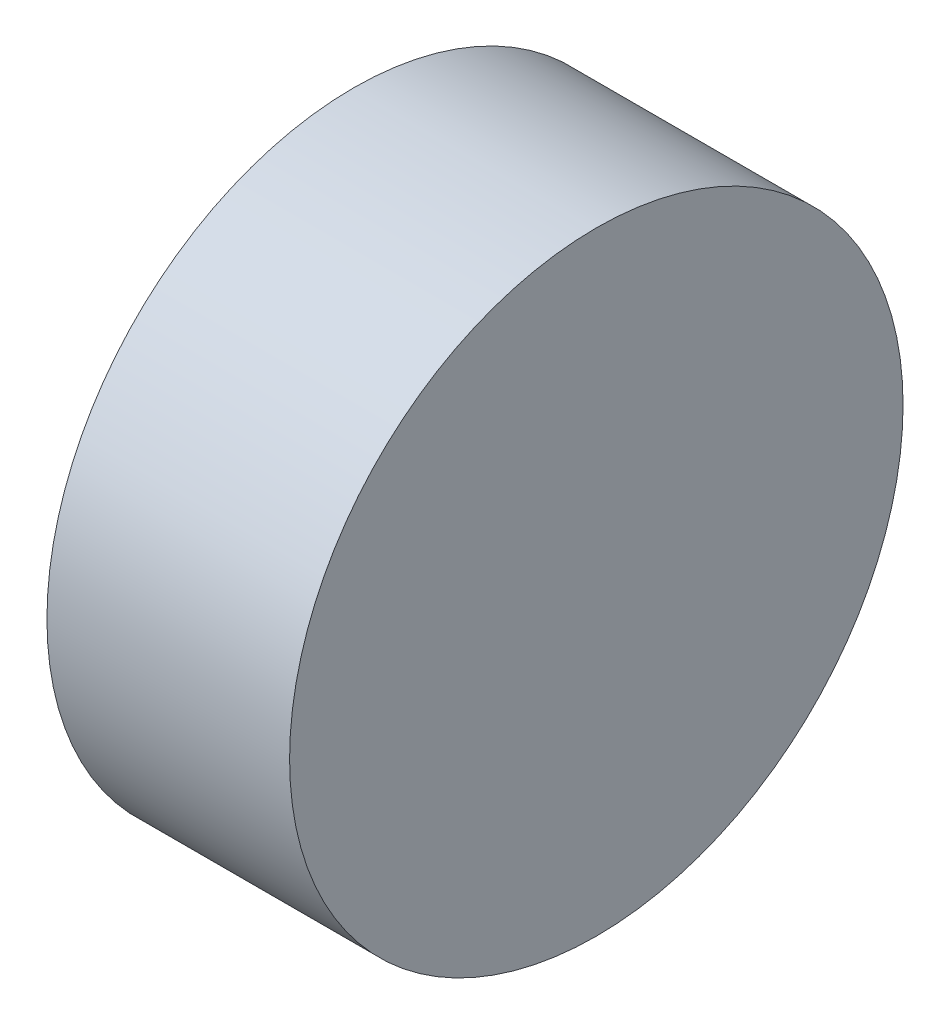
SolidWorks part; units mm, degrees
ref_plane "前视基准面" through (0, 0, 0) normal (0, 0, 1) x (1, 0, 0)
ref_plane "上视基准面" through (0, 0, 0) normal (0, 1, 0) x (1, 0, 0)
ref_plane "右视基准面" through (0, 0, 0) normal (1, 0, 0) x (0, 0, -1)
sketch "草图4" plane through (0, 0, 0) normal (1, 0, 0) x (0, 0, -1)
  circle A0 centre (0, 0) radius 33.5
  dimension "D1" = 67
extrude "凸台-拉伸1" add sketch "草图4" along normal blind 26.5
sketch "草图5" plane through (0, 0, 0) normal (-1, 0, 0) x (0, 0, 1)
  circle A0 centre (0, 0) radius 5.75
  circle A1 centre (0, 0) radius 3
  point P3 (0, 0)
  dimension "D1" = 11.5
  dimension "D2" = 6
extrude "切除-拉伸1" cut sketch "草图5" against normal blind 9 contours A1
sketch "草图6" plane through (0, 0, 0) normal (-1, 0, 0) x (0, 0, 1)
  circle A0 centre (0, 0) radius 3
  circle A1 centre (0, 0) radius 5.75
  dimension "D1" = 11.5
extrude "凸台-拉伸3" add sketch "草图6" along normal blind 2.5
